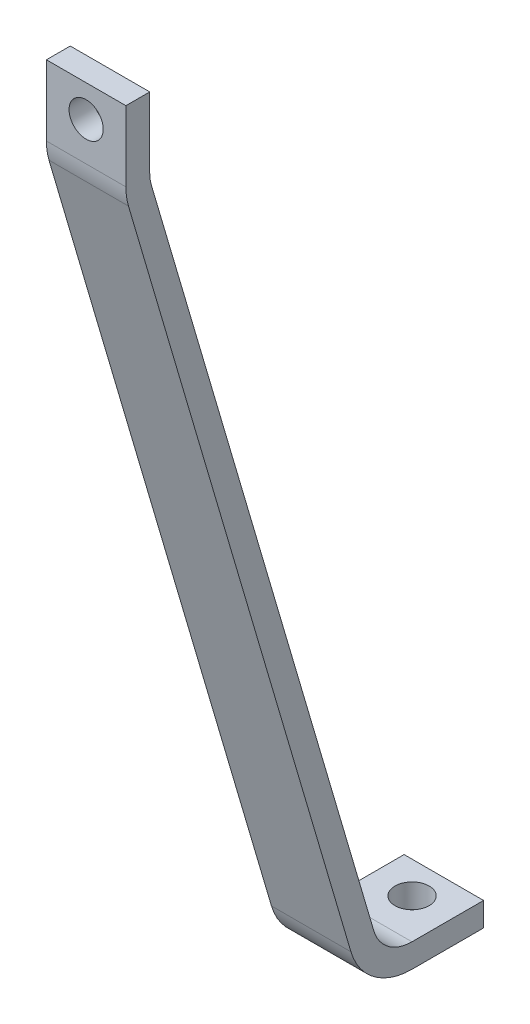
SolidWorks part; units mm, degrees
material "AISI 1045 钢，冷拔"
ref_plane "前视基准面" through (0, 0, 0) normal (0, 0, 1) x (1, 0, 0)
ref_plane "上视基准面" through (0, 0, 0) normal (0, 1, 0) x (1, 0, 0)
ref_plane "右视基准面" through (0, 0, 0) normal (1, 0, 0) x (0, 0, -1)
sketch "草图1" plane through (0, 0, 0) normal (1, 0, 0) x (0, 0, -1)
  line L0 (0, 95.4868) -> (0, 0) construction
  line L1 (0, 112.09) -> (0, 102.09)
  line L2 (0, 102.09) -> (30, 0)
  line L3 (30, 0) -> (45, 0)
  dimension "D1" = 15
  dimension "D2" = 10
  dimension "D3" = 30
  dimension "D4" = 102.09
extrude "拉伸-薄壁1" add sketch "草图1" along normal mid plane 10 thin thin type one direction reverse wall 3
hole_wizard "M4 间隙孔1" positions "草图3" profile "草图2" hole size "M4" standard "GB" end condition up to next
sketch "草图3" plane through (0, 0, -3) normal (0, 0, -1) x (-1, 0, 0)
  line L0 (-5, 112.09) -> (5, 112.09) construction
  point P0 (0, 108.09)
  dimension "D1" = 4
sketch "草图2" plane through (0, 108.09, -3) normal (1, 0, 0) x (0, 1, 0)
  line L0 (0, 0) -> (0, 3)
  line L1 (0, 3) -> (2.15, 3)
  line L2 (2.15, 3) -> (2.15, 0)
  line L5 (2.15, 0) -> (0, 0)
  line L11 (0, -6.35) -> (0, 107.95) construction
  dimension "通孔孔直径" = 4.3
  dimension "通孔孔深度" = 3
hole_wizard "M4 间隙孔2" positions "草图6" profile "草图5" hole size "M4" standard "GB" end condition up to next
sketch "草图6" plane through (0, 0, 0) normal (0, -1, 0) x (-1, 0, 0)
  line L0 (-5, 45) -> (5, 45) construction
  point P0 (0, 41)
  dimension "D1" = 4
sketch "草图5" plane through (0, 0, -41) normal (1, 0, 0) x (0, 0, -1)
  line L0 (0, 0) -> (0, 3)
  line L1 (0, 3) -> (2.15, 3)
  line L2 (2.15, 3) -> (2.15, 0)
  line L5 (2.15, 0) -> (0, 0)
  line L11 (0, -6.35) -> (0, 107.95) construction
  dimension "通孔孔直径" = 4.3
  dimension "通孔孔深度" = 3
